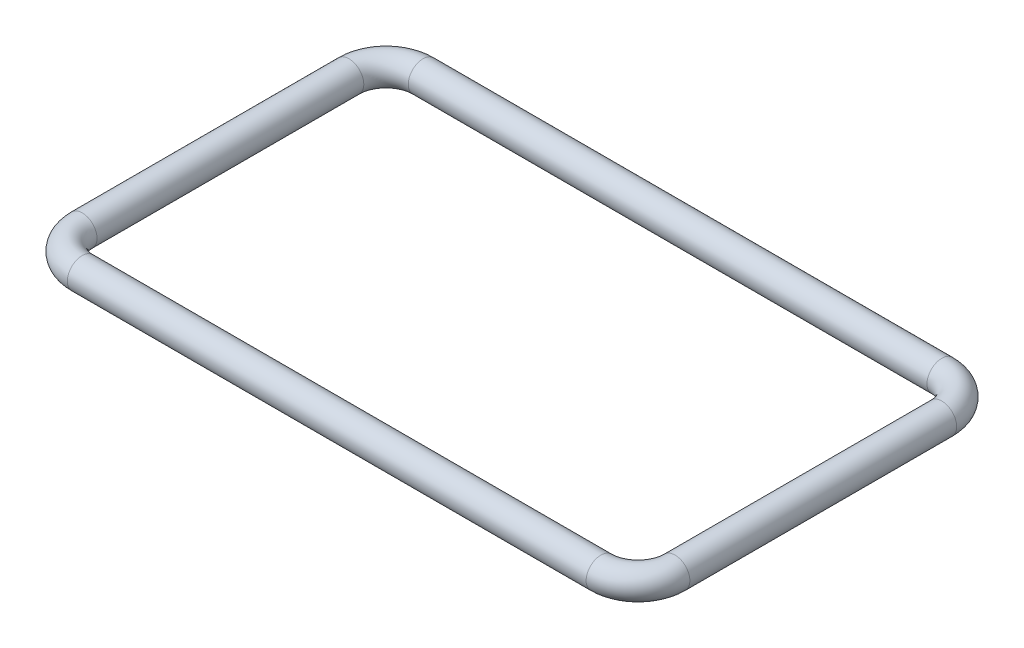
SolidWorks part; units mm, degrees
material "1060 Alloy"
ref_plane "Front Plane" through (0, 0, 0) normal (0, 0, 1) x (1, 0, 0)
ref_plane "Top Plane" through (0, 0, 0) normal (0, 1, 0) x (1, 0, 0)
ref_plane "Right Plane" through (0, 0, 0) normal (1, 0, 0) x (0, 0, -1)
sketch "Sketch1" plane through (0, 0, 0) normal (0, 1, 0) x (1, 0, 0)
  line L1 (0, 0) -> (-22.225, 0)
  line L3 (0, 29.21) -> (-22.225, 29.21)
  line L4 (-25.4, 3.175) -> (-25.4, 26.035)
  arc A0 (-22.225, 0) -> (-25.4, 3.175) centre (-22.225, 3.175) cw
  arc A1 (-22.225, 29.21) -> (-25.4, 26.035) centre (-22.225, 26.035) ccw
  point P7 (-25.4, 0)
  point P10 (-25.4, 29.21)
  dimension "D3" = 3.175
  dimension "D1" = 29.21
  dimension "D2" = 25.4
sweep "Sweep3" add path "Sketch1" circular profile diameter 2.54 parameters "D3"=2.54
mirror "Mirror1" about plane through (0, 0, 0) normal (1, 0, 0) of "Sweep3"
